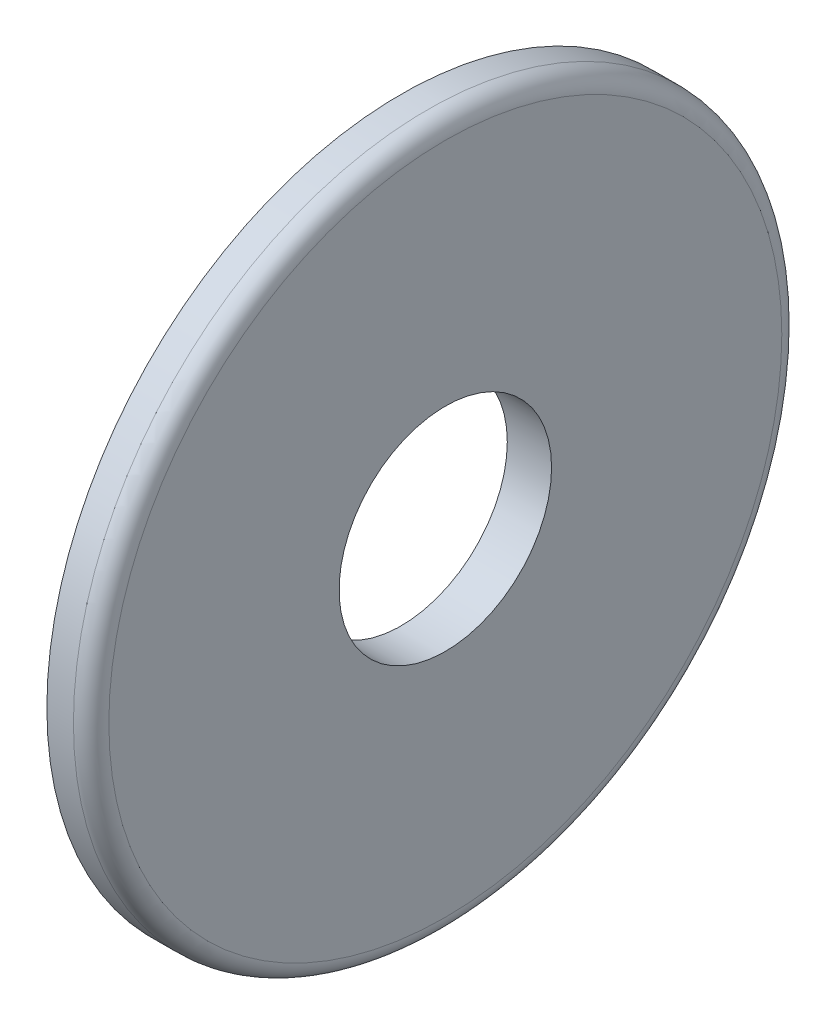
SolidWorks part; units mm, degrees
material "Cast Stainless Steel"
ref_plane "Front Plane" through (0, 0, 0) normal (0, 0, 1) x (1, 0, 0)
ref_plane "Top Plane" through (0, 0, 0) normal (0, 1, 0) x (1, 0, 0)
ref_plane "Right Plane" through (0, 0, 0) normal (1, 0, 0) x (0, 0, -1)
sketch "Sketch1" plane through (0, 0, 0) normal (1, 0, 0) x (0, 0, -1)
  circle A0 centre (0, 0) radius 12.7
  circle A1 centre (0, 0) radius 3.81
  dimension "D1" = 25.4
  dimension "D2" = 7.62
extrude "Boss-Extrude1" add sketch "Sketch1" along normal blind 1.5875
fillet "Fillet1" radius 0.635 1 edges at (1.5875, 0, -12.7)
